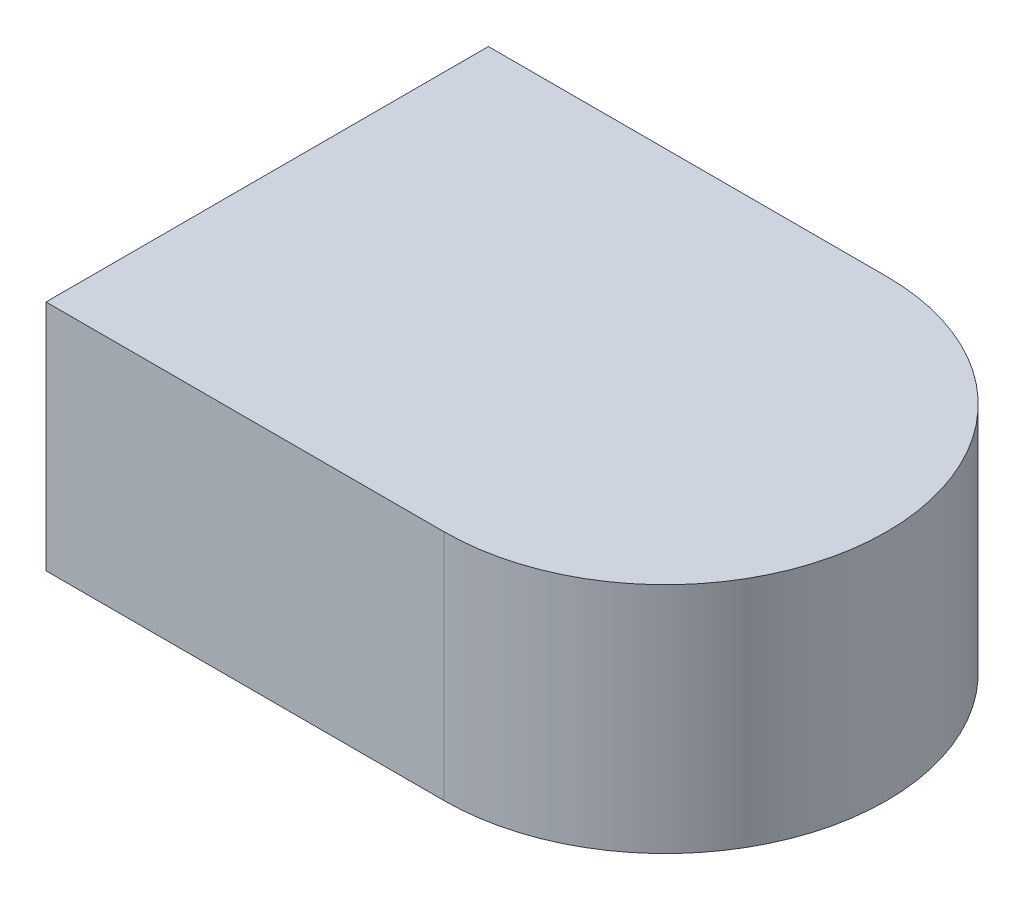
SolidWorks part; units mm, degrees
ref_plane "Front Plane" through (0, 0, 0) normal (0, 0, 1) x (1, 0, 0)
ref_plane "Top Plane" through (0, 0, 0) normal (0, 1, 0) x (1, 0, 0)
ref_plane "Right Plane" through (0, 0, 0) normal (1, 0, 0) x (0, 0, -1)
sketch "Sketch1" plane through (0, 0, 0) normal (0, 1, 0) x (1, 0, 0)
  line L1 (0, 0) -> (17.1, 0)
  line L2 (0, 0) -> (0, 19)
  line L3 (0, 19) -> (17.1, 19)
  line L4 (26.6, 0) -> (26.6, 19) construction
  arc A0 (17.1, 0) -> (17.1, 19) centre (17.1, 9.5) ccw
  dimension "D1" = 19
  dimension "D2" = 26.6
extrude "Boss-Extrude1" add sketch "Sketch1" along normal blind 10
sketch "Sketch3" plane through (0, 0, 0) normal (-1, 0, 0) x (0, 0, 1)
  line L0 (-19, 10) -> (0, 10) construction
  line L1 (0, 10) -> (0, 0) construction
  circle A0 centre (-9.5, 5) radius 4
  point P4 (-9.5, 10)
  point P7 (0, 5)
  dimension "D1" = 8
extrude "Boss-Extrude2" [suppressed] add sketch "Sketch3" against normal blind 70
